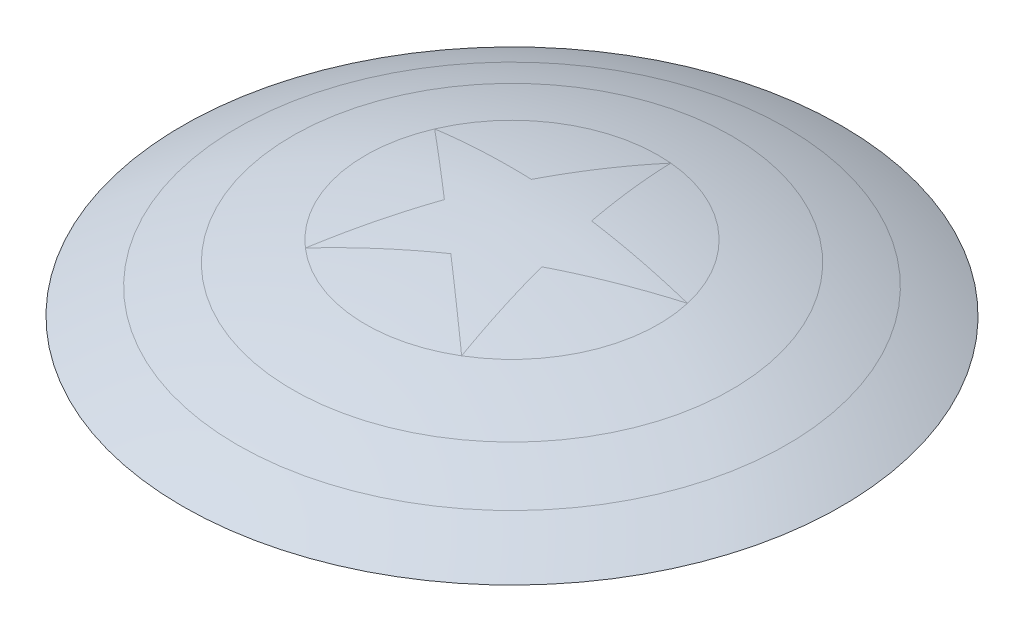
SolidWorks part; units mm, degrees
material "Plain Carbon Steel"
ref_plane "Front Plane" through (0, 0, 0) normal (0, 0, 1) x (1, 0, 0)
ref_plane "Top Plane" through (0, 0, 0) normal (0, 1, 0) x (1, 0, 0)
ref_plane "Right Plane" through (0, 0, 0) normal (1, 0, 0) x (0, 0, -1)
sketch "Sketch2" plane through (0, 0, 0) normal (0, 0, 1) x (1, 0, 0)
  line L0 (0, 0) -> (0, 90)
  line L1 (0, 0) -> (360, 0)
  arc A0 (0, 90) -> (360, 0) centre (-8.7381, -709.9523) cw
  dimension "D3" = 800
  dimension "D1" = 360
  dimension "D2" = 90
revolve "Revolve1" add sketch "Sketch2" angle 360 about L0
ref_plane "Plane1" through (0, 90, 0) normal (0, -1, 0) x (-1, 0, 0)
sketch "Sketch3" plane through (0, 90, 0) normal (0, -1, 0) x (-1, 0, 0)
  line L21 (-155.9423, 35.8049) -> (-56.7107, -24.1527)
  line L27 (-82.2413, -137.2457) -> (-56.7107, -24.1527)
  line L28 (-155.9423, 35.8049) -> (-40.4951, 46.4715)
  line L29 (-14.1364, 159.3743) -> (-40.4951, 46.4715)
  line L30 (-14.1364, 159.3743) -> (31.6833, 52.8736)
  line L31 (147.2056, 62.6939) -> (31.6833, 52.8736)
  line L32 (147.2056, 62.6939) -> (60.0765, -13.7938)
  line L33 (105.1144, -120.6273) -> (60.0765, -13.7938)
  line L34 (105.1144, -120.6273) -> (5.446, -61.3986)
  line L36 (-82.2413, -137.2457) -> (5.446, -61.3986)
  circle A0 centre (0, 0) radius 300
  circle A1 centre (0, 0) radius 240
  circle A2 centre (0, 0) radius 160
  circle A4 centre (0, 0) radius 50 construction
  dimension "D1" = 600
  dimension "D2" = 480
  dimension "D3" = 100
  dimension "D4" = 320
split line "Split Line1"
shell "Shell1" thickness 10
